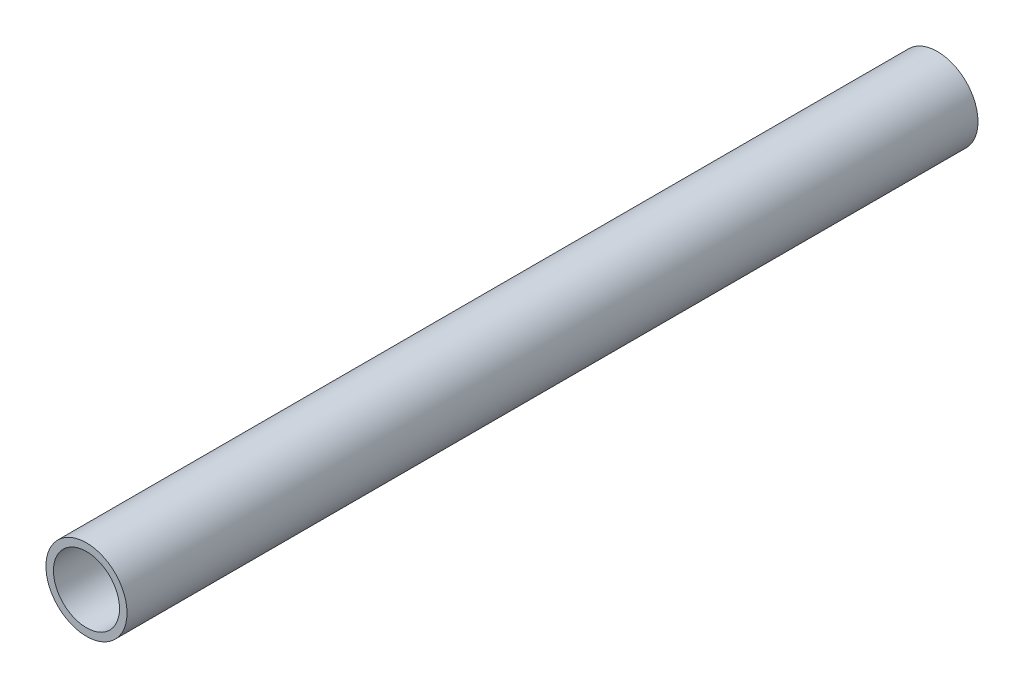
SolidWorks part; units mm, degrees
ref_plane "Alzado" through (0, 0, 0) normal (0, 0, 1) x (1, 0, 0)
ref_plane "Planta" through (0, 0, 0) normal (0, 1, 0) x (1, 0, 0)
ref_plane "Vista lateral" through (0, 0, 0) normal (1, 0, 0) x (0, 0, -1)
sketch "Croquis1" plane through (0, 0, 0) normal (0, 0, 1) x (1, 0, 0)
  circle A0 centre (0, 0) radius 6.6
  circle A1 centre (0, 0) radius 8.1
  dimension "D1" = 16.2
  dimension "D2" = 1.5
extrude "Saliente-Extruir1" add sketch "Croquis1" along normal mid plane 170
